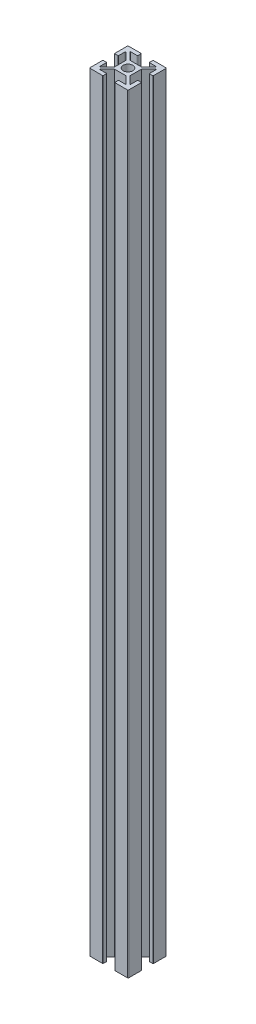
SolidWorks part; units mm, degrees
ref_plane "Front Plane" through (0, 0, 0) normal (0, 0, 1) x (1, 0, 0)
ref_plane "Top Plane" through (0, 0, 0) normal (0, 1, 0) x (1, 0, 0)
ref_plane "Right Plane" through (0, 0, 0) normal (1, 0, 0) x (0, 0, -1)
sketch "Sketch1" plane through (0, 0, 0) normal (0, 1, 0) x (1, 0, 0)
  line L0 (-9.8963, 3) -> (-8.1963, 3)
  line L3 (-3.1963, 10) -> (-9.6963, 10)
  line L4 (-10.0463, 3.15) -> (-10.0463, 9.65)
  line L7 (2.9332, 4) -> (-2.9332, 4)
  line L8 (-4, -2.9454) -> (-4, 2.9454)
  line L9 (-8.0463, 3.15) -> (-8.0463, 6.5862)
  line L10 (-6.6144, 8) -> (-3.1963, 8)
  line L11 (-3.0463, 8.15) -> (-3.0463, 9.85)
  line L12 (-8.0463, 8) -> (-4, 4) construction
  line L13 (-7.7908, 6.6929) -> (-4, 2.9454)
  line L14 (-6.7198, 7.7433) -> (-2.9332, 4)
  line L15 (8.0463, 8) -> (4, 4) construction
  line L22 (0, 0) -> (0, 11.6886) construction
  line L25 (0, 0) -> (-14.9841, 0) construction
  line L27 (6.7198, 7.7433) -> (2.9332, 4)
  line L28 (7.7908, 6.6929) -> (4, 2.9454)
  line L46 (3.0463, 8.15) -> (3.0463, 9.85)
  line L47 (6.6144, 8) -> (3.1963, 8)
  line L48 (8.0463, 3.15) -> (8.0463, 6.5862)
  line L49 (4, -2.9454) -> (4, 2.9454)
  line L50 (10.0463, 3.15) -> (10.0463, 9.65)
  line L51 (3.1963, 10) -> (9.6963, 10)
  line L52 (9.8963, 3) -> (8.1963, 3)
  line L53 (8.0463, -8) -> (4, -4) construction
  line L54 (-8.0463, -8) -> (-4, -4) construction
  line L55 (9.8963, -3) -> (8.1963, -3)
  line L56 (3.1963, -10) -> (9.6963, -10)
  line L57 (10.0463, -3.15) -> (10.0463, -9.65)
  line L58 (8.0463, -3.15) -> (8.0463, -6.5862)
  line L59 (6.6144, -8) -> (3.1963, -8)
  line L60 (3.0463, -8.15) -> (3.0463, -9.85)
  line L61 (7.7908, -6.6929) -> (4, -2.9454)
  line L62 (6.7198, -7.7433) -> (2.9332, -4)
  line L63 (-6.7198, -7.7433) -> (-2.9332, -4)
  line L64 (-7.7908, -6.6929) -> (-4, -2.9454)
  line L65 (-3.0463, -8.15) -> (-3.0463, -9.85)
  line L66 (-6.6144, -8) -> (-3.1963, -8)
  line L67 (-8.0463, -3.15) -> (-8.0463, -6.5862)
  line L68 (2.9332, -4) -> (-2.9332, -4)
  line L69 (-10.0463, -3.15) -> (-10.0463, -9.65)
  line L70 (-3.1963, -10) -> (-9.6963, -10)
  line L71 (-9.8963, -3) -> (-8.1963, -3)
  circle A0 centre (0, 0) radius 2.5
  arc A1 (-10.0463, 9.65) -> (-9.6963, 10) centre (-9.6963, 9.65) cw
  arc A2 (-9.8963, 3) -> (-10.0463, 3.15) centre (-9.8963, 3.15) cw
  arc A3 (-8.1963, 3) -> (-8.0463, 3.15) centre (-8.1963, 3.15) ccw
  arc A4 (-3.1963, 10) -> (-3.0463, 9.85) centre (-3.1963, 9.85) cw
  arc A5 (-3.1963, 8) -> (-3.0463, 8.15) centre (-3.1963, 8.15) ccw
  arc A6 (-6.7198, 7.7433) -> (-6.6144, 8) centre (-6.6144, 7.85) cw
  arc A7 (-7.7908, 6.6929) -> (-8.0463, 6.5862) centre (-7.8963, 6.5862) ccw
  arc A8 (7.7908, 6.6929) -> (8.0463, 6.5862) centre (7.8963, 6.5862) cw
  arc A9 (6.7198, 7.7433) -> (6.6144, 8) centre (6.6144, 7.85) ccw
  arc A10 (3.1963, 8) -> (3.0463, 8.15) centre (3.1963, 8.15) cw
  arc A11 (3.1963, 10) -> (3.0463, 9.85) centre (3.1963, 9.85) ccw
  arc A12 (8.1963, 3) -> (8.0463, 3.15) centre (8.1963, 3.15) cw
  arc A13 (9.8963, 3) -> (10.0463, 3.15) centre (9.8963, 3.15) ccw
  arc A14 (10.0463, 9.65) -> (9.6963, 10) centre (9.6963, 9.65) ccw
  arc A15 (10.0463, -9.65) -> (9.6963, -10) centre (9.6963, -9.65) cw
  arc A16 (9.8963, -3) -> (10.0463, -3.15) centre (9.8963, -3.15) cw
  arc A17 (8.1963, -3) -> (8.0463, -3.15) centre (8.1963, -3.15) ccw
  arc A18 (3.1963, -10) -> (3.0463, -9.85) centre (3.1963, -9.85) cw
  arc A19 (3.1963, -8) -> (3.0463, -8.15) centre (3.1963, -8.15) ccw
  arc A20 (6.7198, -7.7433) -> (6.6144, -8) centre (6.6144, -7.85) cw
  arc A21 (7.7908, -6.6929) -> (8.0463, -6.5862) centre (7.8963, -6.5862) ccw
  arc A22 (-7.7908, -6.6929) -> (-8.0463, -6.5862) centre (-7.8963, -6.5862) cw
  arc A23 (-6.7198, -7.7433) -> (-6.6144, -8) centre (-6.6144, -7.85) ccw
  arc A24 (-3.1963, -8) -> (-3.0463, -8.15) centre (-3.1963, -8.15) cw
  arc A25 (-3.1963, -10) -> (-3.0463, -9.85) centre (-3.1963, -9.85) ccw
  arc A26 (-8.1963, -3) -> (-8.0463, -3.15) centre (-8.1963, -3.15) cw
  arc A27 (-9.8963, -3) -> (-10.0463, -3.15) centre (-9.8963, -3.15) ccw
  arc A28 (-10.0463, -9.65) -> (-9.6963, -10) centre (-9.6963, -9.65) ccw
  point P8 (-10.0463, 10)
  point P27 (-10.0463, 3)
  point P30 (3.0463, 8)
  point P31 (10.0463, -10)
  point P50 (4, 0)
  point P55 (-8.0463, 3)
  point P58 (-3.0463, 10)
  point P61 (-3.0463, 8)
  point P63 (0, 4)
  point P65 (3.0463, 10)
  point P66 (8.0463, 3)
  point P67 (10.0463, 3)
  point P68 (10.0463, 10)
  point P118 (-4, 0)
  point P119 (10.0463, -3)
  point P120 (8.0463, -3)
  point P121 (3.0463, -10)
  point P122 (0, -4)
  point P123 (-3.0463, -8)
  point P124 (-3.0463, -10)
  point P125 (-8.0463, -3)
  point P126 (3.0463, -8)
  point P127 (-10.0463, -3)
  point P128 (-10.0463, -10)
  dimension "D2" = 0.35
  dimension "D3" = 0.15
  dimension "D4" = 0.15
  dimension "D5" = 0.15
  dimension "D12" = 0.15
  dimension "D13" = 0.15
  dimension "D14" = 0.15
  dimension "D6" = 2
  dimension "D7" = 7
  dimension "D8" = 7
  dimension "D9" = 2
  dimension "D10" = 0.75
  dimension "D11" = 0.75
extrude "Boss-Extrude2" add sketch "Sketch1" along normal blind 400
